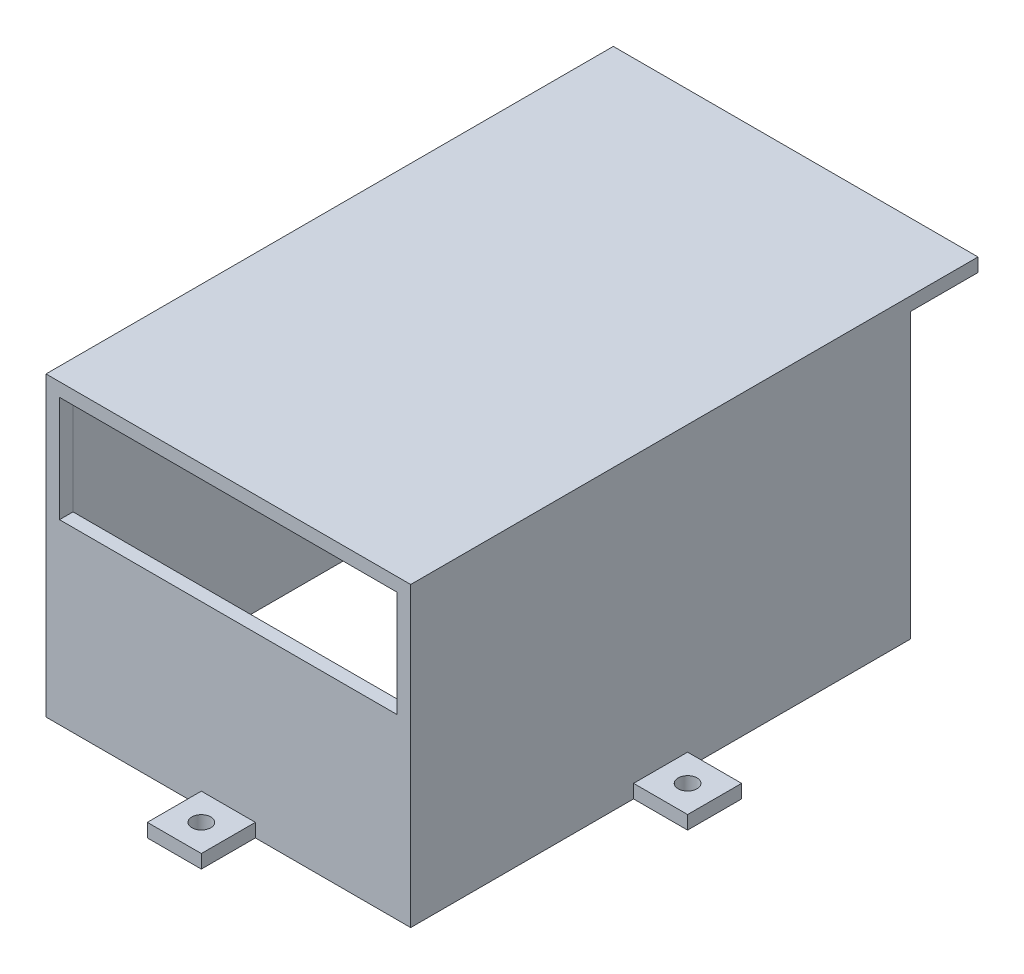
SolidWorks part; units mm, degrees
ref_plane "Front" through (0, 0, 0) normal (0, 0, 1) x (1, 0, 0)
ref_plane "Top" through (0, 0, 0) normal (0, 1, 0) x (1, 0, 0)
ref_plane "Right" through (0, 0, 0) normal (1, 0, 0) x (0, 0, -1)
sketch "草图1" plane through (0, 0, 0) normal (0, 1, 0) x (1, 0, 0)
  line L0 (-13.5, -2) -> (-13.5, -18.5)
  line L1 (12.5, 17.5) -> (-12.5, 17.5)
  line L2 (12.5, 17.5) -> (12.5, -17.5)
  line L3 (12.5, -17.5) -> (-12.5, -17.5)
  line L4 (-12.5, 17.5) -> (-12.5, -17.5)
  line L5 (12.5, 17.5) -> (-12.5, -17.5) construction
  line L6 (12.5, -17.5) -> (-12.5, 17.5) construction
  line L7 (13.5, 18.5) -> (2, 18.5)
  line L8 (13.5, 18.5) -> (13.5, 2)
  line L9 (13.5, -18.5) -> (2, -18.5)
  line L10 (-13.5, 18.5) -> (-13.5, 2)
  line L11 (13.5, 18.5) -> (-13.5, -18.5) construction
  line L12 (13.5, -18.5) -> (-13.5, 18.5) construction
  line L34 (-2, -18.5) -> (-2, -22.5)
  line L35 (-2, -22.5) -> (2, -22.5)
  line L36 (2, -18.5) -> (2, -22.5)
  line L39 (13.5, -2) -> (17.5, -2)
  line L41 (13.5, 2) -> (17.5, 2)
  line L42 (17.5, -2) -> (17.5, 2)
  line L43 (-2, -18.5) -> (-13.5, -18.5)
  line L46 (-2, 18.5) -> (-2, 22.5)
  line L47 (-2, 22.5) -> (2, 22.5)
  line L48 (2, 18.5) -> (2, 22.5)
  line L49 (13.5, -2) -> (13.5, -18.5)
  line L51 (-13.5, 2) -> (-17.5, 2)
  line L53 (-13.5, -2) -> (-17.5, -2)
  line L54 (-17.5, 2) -> (-17.5, -2)
  line L55 (-2, 18.5) -> (-13.5, 18.5)
  circle A0 centre (-15.5, 0) radius 0.7
  circle A2 centre (15.5, 0) radius 0.7
  circle A4 centre (0, 20.5) radius 0.7
  circle A5 centre (0, -20.5) radius 0.7
  point P0 (0, 0)
  point P6 (0, 0)
  point P11 (0, -18.5)
  point P16 (13.5, 0)
  point P21 (0, 18.5)
  point P26 (-13.5, 0)
  dimension "D1" = 35
  dimension "D2" = 25
  dimension "D3" = 27
  dimension "D4" = 37
extrude "凸台-拉伸1" add sketch "草图1" along normal blind 1
sketch "草图3" plane through (0, 1, 0) normal (0, 1, 0) x (1, 0, 0)
  line L1 (12.5, 17.5) -> (-12.5, 17.5)
  line L2 (12.5, 17.5) -> (12.5, -17.5)
  line L3 (12.5, -17.5) -> (-12.5, -17.5)
  line L4 (-12.5, 17.5) -> (-12.5, -17.5)
  line L5 (12.5, 17.5) -> (-12.5, -17.5) construction
  line L6 (12.5, -17.5) -> (-12.5, 17.5) construction
  line L7 (13.5, 18.5) -> (-13.5, 18.5)
  line L8 (13.5, 18.5) -> (13.5, -18.5)
  line L9 (13.5, -18.5) -> (-13.5, -18.5)
  line L10 (-13.5, 18.5) -> (-13.5, -18.5)
  line L11 (13.5, 18.5) -> (-13.5, -18.5) construction
  line L12 (13.5, -18.5) -> (-13.5, 18.5) construction
  point P0 (0, 0)
  point P7 (0, 0)
extrude "凸台-拉伸2" add sketch "草图3" along normal blind 20
sketch "草图4" plane through (0, 21, 0) normal (0, 1, 0) x (1, 0, 0)
  line L1 (13.5, 18.5) -> (-13.5, 18.5)
  line L2 (13.5, 18.5) -> (13.5, -18.5)
  line L3 (13.5, -18.5) -> (-13.5, -18.5)
  line L4 (-13.5, 18.5) -> (-13.5, -18.5)
  line L5 (13.5, 18.5) -> (-13.5, -18.5) construction
  line L6 (13.5, -18.5) -> (-13.5, 18.5) construction
  point P0 (0, 0)
extrude "凸台-拉伸3" add sketch "草图4" along normal blind 1
sketch "草图5" plane through (0, 0, 0) normal (0, 0, 1) x (1, 0, 0)
  line L1 (-12.5, 21) -> (12.5, 21)
  line L2 (-12.5, 21) -> (-12.5, 13.1547)
  line L3 (-12.5, 13.1547) -> (12.5, 13.1547)
  line L4 (12.5, 21) -> (12.5, 13.1547)
extrude "切除-拉伸1" cut sketch "草图5" against normal through all both and the other way through all
ref_plane "基准面1" through (0, 0, -18.5) normal (0, 0, -1) x (-1, 0, 0)
sketch "草图6" plane through (0, 0, -18.5) normal (0, 0, -1) x (-1, 0, 0)
  line L5 (-13.5, 22) -> (13.5001, 22)
  line L6 (-13.5, 22) -> (-13.5, 21.0002)
  line L7 (-13.5, 21.0002) -> (13.5001, 21.0002)
  line L8 (13.5001, 22) -> (13.5001, 21.0002)
extrude "凸台-拉伸4" add sketch "草图6" along normal blind 5
